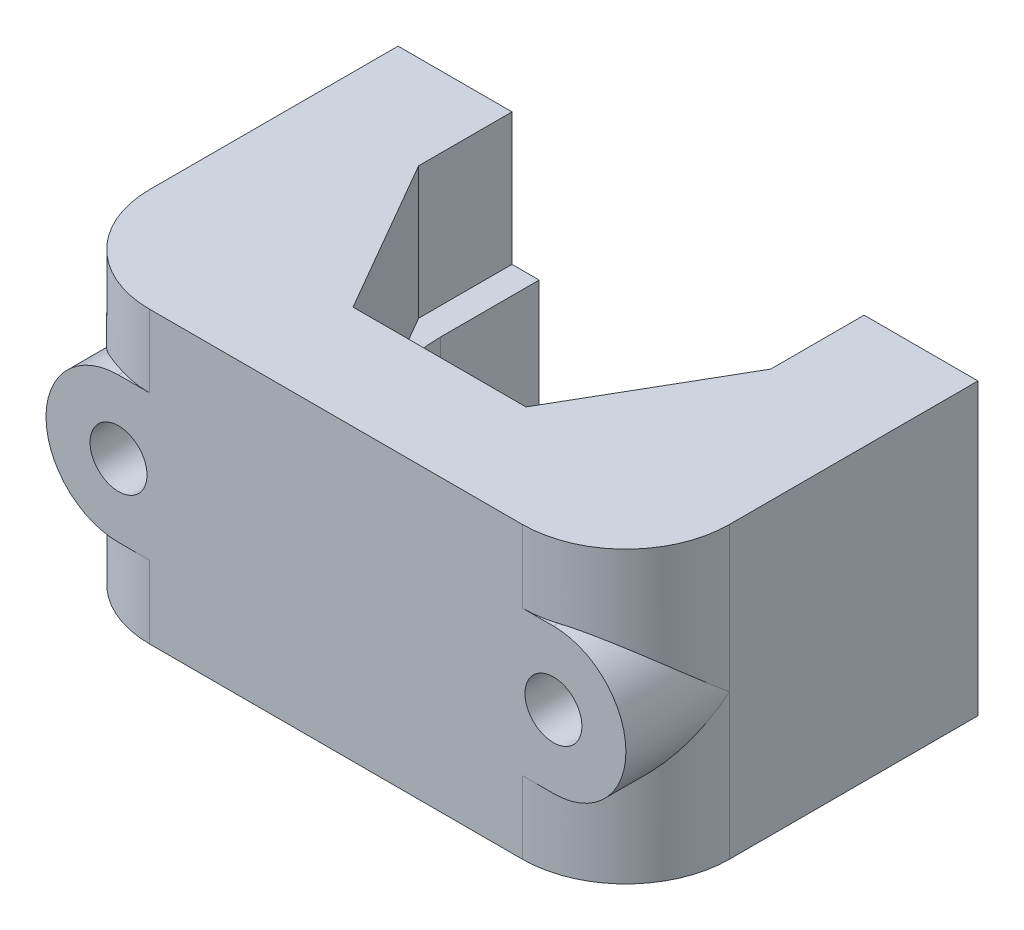
SolidWorks part; units mm, degrees
other "Markup1"
sketch "Sketch7" plane through (-25, 28, 17) normal (-0.0337, 0.6437, 0.7645) x (0.9929, 0.1091, -0.048)
material "ABS"
ref_plane "Front" through (0, 0, 0) normal (0, 0, 1) x (1, 0, 0)
ref_plane "Top" through (0, 0, 0) normal (0, 1, 0) x (1, 0, 0)
ref_plane "Right" through (0, 0, 0) normal (1, 0, 0) x (0, 0, -1)
sketch "Sketch1" plane through (0, 0, 0) normal (0, 1, 0) x (1, 0, 0)
  line L1 (-28, -17) -> (28, -17)
  line L2 (-28, -17) -> (-28, 17)
  line L3 (-28, 17) -> (28, 17)
  line L4 (28, -17) -> (28, 17)
  line L5 (-28, -17) -> (28, 17) construction
  line L6 (-28, 17) -> (28, -17) construction
  point P0 (0, 0)
  dimension "D1" = 56
  dimension "D2" = 34
extrude "Boss-Extrude1" add sketch "Sketch1" along normal blind 28
sketch "Sketch2" plane through (0, 28, 0) normal (0, 1, 0) x (1, 0, 0)
  line L3 (-17, 7.9822) -> (-8.35, -7)
  line L4 (-8.35, -7) -> (8.35, -7)
  line L5 (8.35, -7) -> (17, 7.9822)
  line L7 (-28, -17) -> (28, -17) construction
  line L9 (-17, 7.9822) -> (-17, 17)
  line L10 (28, 17) -> (-28, 17) construction
  line L11 (17, 7.9822) -> (17, 17)
  line L12 (-17, 17) -> (17, 17)
  line L14 (-8.35, 21.9252) -> (-12.525, 14.6939) [skipped]
  line L15 (16.7, 7.4626) -> (12.525, 14.6939) [skipped]
  line L16 (8.35, 21.9252) -> (-8.35, 21.9252) [skipped]
  arc A0 (-12.525, 0.2313) -> (12.525, 0.2313) centre (0, 7.4626) ccw construction
  dimension "D1" = 16.7
  dimension "D2" = 10
  dimension "D3" = 34
extrude "Cut-Extrude1" cut sketch "Sketch2" against normal blind 12.75
sketch "Sketch3" plane through (0, 15.25, 0) normal (0, 1, 0) x (1, 0, 0)
  line L0 (-14.375, 7.4626) -> (-14.375, 17)
  line L1 (17, 17) -> (-17, 17) construction
  line L2 (14.375, 7.4626) -> (14.375, 17)
  line L3 (-14.375, 17) -> (14.375, 17)
  arc A0 (-14.375, 7.4626) -> (14.375, 7.4626) centre (0, 7.4626) ccw
  dimension "D1" = 28.75
extrude "Cut-Extrude2" cut sketch "Sketch3" against normal up to surface (15.25 mm away) up to face at (0, 0, 0)
fillet "Fillet1" radius 10 2 edges at (28, 14, 17) (-28, 14, 17)
sketch "Sketch5" plane through (0, 0, 7) normal (0, 0, -1) x (-1, 0, 0)
  line L0 (18, 21) -> (18, 7)
  line L1 (18, 28) -> (18, 0) construction
  line L2 (-18, 14) -> (18, 14) construction
  line L3 (-18, 0) -> (-18, 28) construction
  line L4 (18, 21) -> (21, 21)
  line L5 (18, 7) -> (21, 7)
  line L6 (28, 0) -> (28, 28) construction
  line L7 (0, 50) -> (0, -50) construction
  line L8 (-18, 7) -> (-21, 7)
  line L9 (-18, 21) -> (-18, 7)
  line L10 (-18, 21) -> (-21, 21)
  arc A1 (21, 21) -> (21, 7) centre (21, 14) cw
  arc A2 (-21, 21) -> (-21, 7) centre (-21, 14) ccw
  point P6 (28, 14)
  point P14 (28, 14)
  dimension "D1" = 14
extrude "Boss-Extrude2" add sketch "Sketch5" against normal up to surface (10 mm away) up to face at (0, 14, 17)
sketch "Sketch6" plane through (0, 0, 17) normal (0, 0, 1) x (1, 0, 0)
  line L0 (-28, 14) -> (-28, 28) construction
  circle A0 centre (-21, 14) radius 2.75
  circle A1 centre (21, 14) radius 2.75
  dimension "D1" = 5.5
  dimension "D2" = 7
extrude "Cut-Extrude3" cut sketch "Sketch6" against normal up to surface (34 mm away) up to face at (-19.7917, 14.4167, -17)
